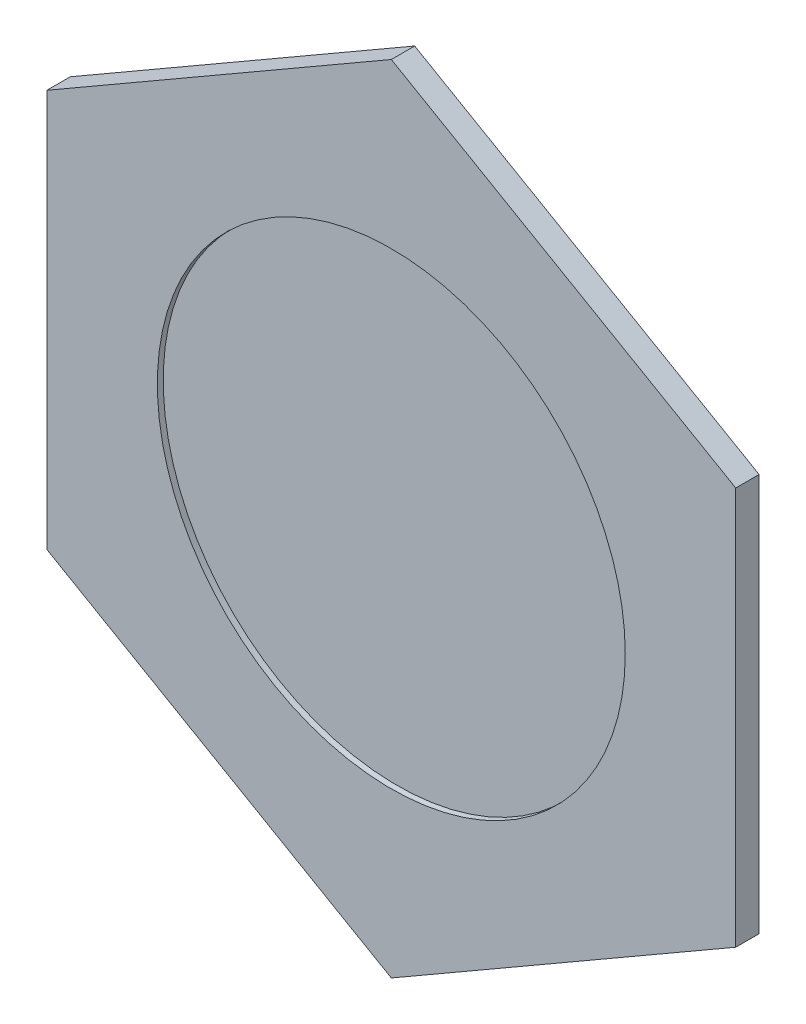
SolidWorks part; units mm, degrees
ref_plane "정면" through (0, 0, 0) normal (0, 0, 1) x (1, 0, 0)
ref_plane "윗면" through (0, 0, 0) normal (0, 1, 0) x (1, 0, 0)
ref_plane "우측면" through (0, 0, 0) normal (1, 0, 0) x (0, 0, -1)
sketch "스케치1" plane through (0, 0, 0) normal (0, 0, 1) x (1, 0, 0)
  line L0 (0, 0) -> (-56.2917, 32.5)
  line L1 (58.8897, -34) -> (58.8897, 34)
  line L2 (58.8897, 34) -> (0, 68)
  line L3 (0, 68) -> (-58.8897, 34)
  line L4 (-58.8897, 34) -> (-58.8897, -34)
  line L5 (-58.8897, -34) -> (0, -68)
  line L6 (0, -68) -> (58.8897, -34)
  line L7 (56.2917, 32.5) -> (0, 0)
  line L8 (0, -65) -> (0, 0)
  line L9 (-56.2917, 32.5) -> (-56.2917, -32.5)
  line L10 (-56.2917, -32.5) -> (0, -65)
  line L11 (0, -65) -> (56.2917, -32.5)
  line L12 (56.2917, -32.5) -> (56.2917, 32.5)
  line L13 (56.2917, 32.5) -> (0, 65)
  line L14 (0, 65) -> (-56.2917, 32.5)
  circle A1 centre (0, 0) radius 58.8897 construction
  point P1 (-58, 34.641)
  point P11 (0, -5)
  point P15 (0, -10)
  point P17 (-59, 32.909)
  point P20 (0, -15)
  point P21 (0, -20)
  point P22 (0, -25)
  point P23 (0, -30)
  point P24 (0, -35)
  point P25 (0, -40)
  point P26 (0, -45)
  point P27 (0, -50)
  point P28 (0, -55)
  point P29 (0, -60)
  point P32 (-4.3301, 2.3594)
  point P33 (-8.6603, 4.8594)
  point P34 (-12.9904, 7.3594)
  point P35 (-17.3205, 9.8594)
  point P36 (-21.6506, 12.3594)
  point P37 (-25.9808, 14.8594)
  point P38 (-30.3109, 17.3594)
  point P39 (-34.641, 19.8594)
  point P40 (-38.9711, 22.3594)
  point P41 (-43.3013, 24.8594)
  point P42 (-47.6314, 27.3594)
  point P43 (-51.9615, 29.8594)
  point P44 (4.2083, 2.4297)
  point P45 (8.5385, 4.9297)
  point P46 (12.8686, 7.4297)
  point P47 (17.1987, 9.9297)
  point P48 (21.5289, 12.4297)
  point P49 (25.859, 14.9297)
  point P50 (30.1891, 17.4297)
  point P51 (34.5192, 19.9297)
  point P52 (38.8494, 22.4297)
  point P53 (43.1795, 24.9297)
  point P54 (47.5096, 27.4297)
  point P55 (51.8397, 29.9297)
  point P56 (-0.0406, -0.0703)
  dimension "D1" = 65
  dimension "D2" = 5
  dimension "D3" = 12
  dimension "D4" = 3
  dimension "D5" = 65
  dimension "D6" = 65
  dimension "D7" = 65
  dimension "D8" = 68
extrude "보스-돌출1" add sketch "스케치1" along normal blind 4 contours L4 L5 L6 L1 L2 L3
sketch "스케치2" plane through (0, 0, 4) normal (0, 0, 1) x (1, 0, 0)
  circle A0 centre (0, 0) radius 40
  dimension "D1" = 80
extrude "컷-돌출1" cut sketch "스케치2" against normal blind 1
sketch "스케치4" plane through (0, 0, 4) normal (0, 0, 1) x (1, 0, 0)
  line L0 (0, 0) -> (0, -68)
  line L1 (0, 0) -> (-58.8897, 34)
  line L2 (0, 0) -> (58.8897, 34)
  line L3 (-58.8897, 34) -> (-58.8897, -34)
  line L4 (-58.8897, -34) -> (0, -68)
  line L5 (58.8897, -34) -> (0, -68)
  line L6 (58.8897, 34) -> (58.8897, -34)
  line L7 (58.8897, 34) -> (0, 68)
  line L8 (0, 68) -> (-58.8897, 34)
  line L9 (-56.3897, 32.5566) -> (56.3897, 32.5566) construction
  line L10 (0, 68) -> (0, 0)
  line L11 (-28.1949, -48.8349) -> (28.1949, 48.8349) construction
  line L12 (-58.8897, -34) -> (0, 0)
  line L13 (58.8897, -34) -> (0, 0)
  line L14 (0, 65.1132) -> (-56.3897, 32.5566)
  line L15 (56.3897, 32.5566) -> (0, 65.1132)
  line L16 (56.3897, -32.5566) -> (56.3897, 32.5566)
  line L17 (0, -65.1132) -> (56.3897, -32.5566)
  line L18 (-56.3897, -32.5566) -> (0, -65.1132)
  line L19 (-56.3897, 32.5566) -> (-56.3897, -32.5566)
  line L20 (-56.3897, 32.5566) -> (0, -65.1132) construction
  line L21 (56.3897, 32.5566) -> (0, -65.1132) construction
  line L22 (0, 65.1132) -> (56.3897, -32.5566) construction
  line L23 (-56.3897, -32.5566) -> (56.3897, -32.5566) construction
  line L24 (0, 65.1132) -> (-56.3897, -32.5566) construction
  line L25 (0, -65.1132) -> (-4.3301, -2.5)
  line L26 (0, -60) -> (-8.6603, -5)
  line L27 (0, -55) -> (-12.9904, -7.5)
  line L28 (0, -50) -> (-17.3205, -10)
  line L29 (0, -45) -> (-21.6506, -12.5)
  line L30 (0, -40) -> (-25.9808, -15)
  line L31 (0, -35) -> (-30.3109, -17.5)
  line L32 (0, -30) -> (-34.641, -20)
  line L33 (0, -25) -> (-38.9711, -22.5)
  line L34 (0, -20) -> (-43.3013, -25)
  line L35 (0, -15) -> (-47.6314, -27.5)
  line L36 (0, -10) -> (-51.9615, -30)
  line L37 (0, -5) -> (-56.3897, -32.5566)
  line L38 (-56.3897, -32.5566) -> (0, -60)
  line L39 (-51.9615, -35.1132) -> (0, -55)
  line L40 (-47.6314, -37.6132) -> (0, -50)
  line L41 (-43.3013, -40.1132) -> (0, -45)
  line L42 (-38.9711, -42.6132) -> (0, -40)
  line L43 (-34.641, -45.1132) -> (0, -35)
  line L44 (-30.3109, -47.6132) -> (0, -30)
  line L45 (-25.9808, -50.1132) -> (0, -25)
  line L46 (-21.6506, -52.6132) -> (0, -20)
  line L47 (-17.3205, -55.1132) -> (0, -15)
  line L48 (-12.9904, -57.6132) -> (0, -10)
  line L49 (-8.6603, -60.1132) -> (0, -5)
  line L50 (-4.3301, -62.6132) -> (0, 0)
  line L51 (-52.0596, -35.0566) -> (0, 0)
  line L52 (-47.7295, -37.5566) -> (-4.3301, -2.5)
  line L53 (-43.3993, -40.0566) -> (-8.6603, -5)
  line L54 (-39.0692, -42.5566) -> (-12.9904, -7.5)
  line L55 (-34.7391, -45.0566) -> (-17.3205, -10)
  line L56 (-30.409, -47.5566) -> (-21.6506, -12.5)
  line L57 (-26.0788, -50.0566) -> (-25.9808, -15)
  line L58 (-21.7487, -52.5566) -> (-30.3109, -17.5)
  line L59 (-17.4186, -55.0566) -> (-34.641, -20)
  line L60 (-13.0885, -57.5566) -> (-38.9711, -22.5)
  line L61 (-8.7583, -60.0566) -> (-43.3013, -25)
  line L62 (-4.4282, -62.5566) -> (-47.6314, -27.5)
  line L63 (0, -65.1132) -> (-51.9615, -30)
  line L64 (-56.3897, -32.5566) -> (-4.3301, 2.5)
  line L65 (-51.9615, -30) -> (-8.6603, 5)
  line L66 (-47.6314, -27.5) -> (-12.9904, 7.5)
  line L67 (-43.3013, -25) -> (-17.3205, 10)
  line L68 (-38.9711, -22.5) -> (-21.6506, 12.5)
  line L69 (-34.641, -20) -> (-25.9808, 15)
  line L70 (-30.3109, -17.5) -> (-30.3109, 17.5)
  line L71 (-25.9808, -15) -> (-34.641, 20)
  line L72 (-21.6506, -12.5) -> (-38.9711, 22.5)
  line L73 (-17.3205, -10) -> (-43.3013, 25)
  line L74 (-12.9904, -7.5) -> (-47.6314, 27.5)
  line L75 (-8.6603, -5) -> (-51.9615, 30)
  line L76 (-4.3301, -2.5) -> (-56.3897, 32.5566)
  line L77 (-56.3897, 32.5566) -> (-51.9615, -30)
  line L78 (-56.3897, 27.4434) -> (-47.6314, -27.5)
  line L79 (-56.3897, 22.4434) -> (-43.3013, -25)
  line L80 (-56.3897, 17.4434) -> (-38.9711, -22.5)
  line L81 (-56.3897, 12.4434) -> (-34.641, -20)
  line L82 (-56.3897, 7.4434) -> (-30.3109, -17.5)
  line L83 (-56.3897, 2.4434) -> (-25.9808, -15)
  line L84 (-56.3897, -2.5566) -> (-21.6506, -12.5)
  line L85 (-56.3897, -7.5566) -> (-17.3205, -10)
  line L86 (-56.3897, -12.5566) -> (-12.9904, -7.5)
  line L87 (-56.3897, -17.5566) -> (-8.6603, -5)
  line L88 (-56.3897, -22.5566) -> (-4.3301, -2.5)
  line L89 (-56.3897, -27.5566) -> (0, 0)
  line L90 (-56.3897, 27.5566) -> (0, 0)
  line L91 (-56.3897, 22.5566) -> (-4.3301, 2.5)
  line L92 (-56.3897, 17.5566) -> (-8.6603, 5)
  line L93 (-56.3897, 12.5566) -> (-12.9904, 7.5)
  line L94 (-56.3897, 7.5566) -> (-17.3205, 10)
  line L95 (-56.3897, 2.5566) -> (-21.6506, 12.5)
  line L96 (-56.3897, -2.4434) -> (-25.9808, 15)
  line L97 (-56.3897, -7.4434) -> (-30.3109, 17.5)
  line L98 (-56.3897, -12.4434) -> (-34.641, 20)
  line L99 (-56.3897, -17.4434) -> (-38.9711, 22.5)
  line L100 (-56.3897, -22.4434) -> (-43.3013, 25)
  line L101 (-56.3897, -27.4434) -> (-47.6314, 27.5)
  line L102 (-56.3897, -32.5566) -> (-51.9615, 30)
  line L103 (-56.3897, 32.5566) -> (0, 5)
  line L104 (-51.9615, 30) -> (0, 10)
  line L105 (-47.6314, 27.5) -> (0, 15)
  line L106 (-43.3013, 25) -> (0, 20)
  line L107 (-38.9711, 22.5) -> (0, 25)
  line L108 (-34.641, 20) -> (0, 30)
  line L109 (-30.3109, 17.5) -> (0, 35)
  line L110 (-25.9808, 15) -> (0, 40)
  line L111 (-21.6506, 12.5) -> (0, 45)
  line L112 (-17.3205, 10) -> (0, 50)
  line L113 (-12.9904, 7.5) -> (0, 55)
  line L114 (-8.6603, 5) -> (0, 60)
  line L115 (-4.3301, 2.5) -> (0, 65.1132)
  line L116 (0, 65.1132) -> (-51.9615, 30)
  line L117 (-4.4282, 62.5566) -> (-47.6314, 27.5)
  line L118 (-8.7583, 60.0566) -> (-43.3013, 25)
  line L119 (-13.0885, 57.5566) -> (-38.9711, 22.5)
  line L120 (-17.4186, 55.0566) -> (-34.641, 20)
  line L121 (-21.7487, 52.5566) -> (-30.3109, 17.5)
  line L122 (-26.0788, 50.0566) -> (-25.9808, 15)
  line L123 (-30.409, 47.5566) -> (-21.6506, 12.5)
  line L124 (-34.7391, 45.0566) -> (-17.3205, 10)
  line L125 (-39.0692, 42.5566) -> (-12.9904, 7.5)
  line L126 (-43.3993, 40.0566) -> (-8.6603, 5)
  line L127 (-47.7295, 37.5566) -> (-4.3301, 2.5)
  line L128 (-52.0596, 35.0566) -> (0, 0)
  line L129 (-4.3301, 62.6132) -> (0, 0)
  line L130 (-8.6603, 60.1132) -> (0, 5)
  line L131 (-12.9904, 57.6132) -> (0, 10)
  line L132 (-17.3205, 55.1132) -> (0, 15)
  line L133 (-21.6506, 52.6132) -> (0, 20)
  line L134 (-25.9808, 50.1132) -> (0, 25)
  line L135 (-30.3109, 47.6132) -> (0, 30)
  line L136 (-34.641, 45.1132) -> (0, 35)
  line L137 (-38.9711, 42.6132) -> (0, 40)
  line L138 (-43.3013, 40.1132) -> (0, 45)
  line L139 (-47.6314, 37.6132) -> (0, 50)
  line L140 (-51.9615, 35.1132) -> (0, 55)
  line L141 (-56.3897, 32.5566) -> (0, 60)
  line L142 (0, 65.1132) -> (4.3301, 2.5)
  line L143 (0, 60) -> (8.6603, 5)
  line L144 (0, 55) -> (12.9904, 7.5)
  line L145 (0, 50) -> (17.3205, 10)
  line L146 (0, 45) -> (21.6506, 12.5)
  line L147 (0, 40) -> (25.9808, 15)
  line L148 (0, 35) -> (30.3109, 17.5)
  line L149 (0, 30) -> (34.641, 20)
  line L150 (0, 25) -> (38.9711, 22.5)
  line L151 (0, 20) -> (43.3013, 25)
  line L152 (0, 15) -> (47.6314, 27.5)
  line L153 (0, 10) -> (51.9615, 30)
  line L154 (0, 5) -> (56.3897, 32.5566)
  line L155 (56.3897, 32.5566) -> (0, 60)
  line L156 (51.9615, 35.1132) -> (0, 55)
  line L157 (47.6314, 37.6132) -> (0, 50)
  line L158 (43.3013, 40.1132) -> (0, 45)
  line L159 (38.9711, 42.6132) -> (0, 40)
  line L160 (34.641, 45.1132) -> (0, 35)
  line L161 (30.3109, 47.6132) -> (0, 30)
  line L162 (25.9808, 50.1132) -> (0, 25)
  line L163 (21.6506, 52.6132) -> (0, 20)
  line L164 (17.3205, 55.1132) -> (0, 15)
  line L165 (12.9904, 57.6132) -> (0, 10)
  line L166 (8.6603, 60.1132) -> (0, 5)
  line L167 (4.3301, 62.6132) -> (0, 0)
  line L168 (52.0596, 35.0566) -> (0, 0)
  line L169 (47.7295, 37.5566) -> (4.3301, 2.5)
  line L170 (43.3993, 40.0566) -> (8.6603, 5)
  line L171 (39.0692, 42.5566) -> (12.9904, 7.5)
  line L172 (34.7391, 45.0566) -> (17.3205, 10)
  line L173 (30.409, 47.5566) -> (21.6506, 12.5)
  line L174 (26.0788, 50.0566) -> (25.9808, 15)
  line L175 (21.7487, 52.5566) -> (30.3109, 17.5)
  line L176 (17.4186, 55.0566) -> (34.641, 20)
  line L177 (13.0885, 57.5566) -> (38.9711, 22.5)
  line L178 (8.7583, 60.0566) -> (43.3013, 25)
  line L179 (4.4282, 62.5566) -> (47.6314, 27.5)
  line L180 (0, 65.1132) -> (51.9615, 30)
  line L181 (56.3897, 32.5566) -> (4.3301, -2.5)
  line L182 (51.9615, 30) -> (8.6603, -5)
  line L183 (47.6314, 27.5) -> (12.9904, -7.5)
  line L184 (43.3013, 25) -> (17.3205, -10)
  line L185 (38.9711, 22.5) -> (21.6506, -12.5)
  line L186 (34.641, 20) -> (25.9808, -15)
  line L187 (30.3109, 17.5) -> (30.3109, -17.5)
  line L188 (25.9808, 15) -> (34.641, -20)
  line L189 (21.6506, 12.5) -> (38.9711, -22.5)
  line L190 (17.3205, 10) -> (43.3013, -25)
  line L191 (12.9904, 7.5) -> (47.6314, -27.5)
  line L192 (8.6603, 5) -> (51.9615, -30)
  line L193 (4.3301, 2.5) -> (56.3897, -32.5566)
  line L194 (56.3897, -32.5566) -> (51.9615, 30)
  line L195 (56.3897, -27.4434) -> (47.6314, 27.5)
  line L196 (56.3897, -22.4434) -> (43.3013, 25)
  line L197 (56.3897, -17.4434) -> (38.9711, 22.5)
  line L198 (56.3897, -12.4434) -> (34.641, 20)
  line L199 (56.3897, -7.4434) -> (30.3109, 17.5)
  line L200 (56.3897, -2.4434) -> (25.9808, 15)
  line L201 (56.3897, 2.5566) -> (21.6506, 12.5)
  line L202 (56.3897, 7.5566) -> (17.3205, 10)
  line L203 (56.3897, 12.5566) -> (12.9904, 7.5)
  line L204 (56.3897, 17.5566) -> (8.6603, 5)
  line L205 (56.3897, 22.5566) -> (4.3301, 2.5)
  line L206 (56.3897, 27.5566) -> (0, 0)
  line L207 (56.3897, -27.5566) -> (0, 0)
  line L208 (56.3897, -22.5566) -> (4.3301, -2.5)
  line L209 (56.3897, -17.5566) -> (8.6603, -5)
  line L210 (56.3897, -12.5566) -> (12.9904, -7.5)
  line L211 (56.3897, -7.5566) -> (17.3205, -10)
  line L212 (56.3897, -2.5566) -> (21.6506, -12.5)
  line L213 (56.3897, 2.4434) -> (25.9808, -15)
  line L214 (56.3897, 7.4434) -> (30.3109, -17.5)
  line L215 (56.3897, 12.4434) -> (34.641, -20)
  line L216 (56.3897, 17.4434) -> (38.9711, -22.5)
  line L217 (56.3897, 22.4434) -> (43.3013, -25)
  line L218 (56.3897, 27.4434) -> (47.6314, -27.5)
  line L219 (56.3897, 32.5566) -> (51.9615, -30)
  line L220 (56.3897, -32.5566) -> (0, -5)
  line L221 (51.9615, -30) -> (0, -10)
  line L222 (47.6314, -27.5) -> (0, -15)
  line L223 (43.3013, -25) -> (0, -20)
  line L224 (38.9711, -22.5) -> (0, -25)
  line L225 (34.641, -20) -> (0, -30)
  line L226 (30.3109, -17.5) -> (0, -35)
  line L227 (25.9808, -15) -> (0, -40)
  line L228 (21.6506, -12.5) -> (0, -45)
  line L229 (17.3205, -10) -> (0, -50)
  line L230 (12.9904, -7.5) -> (0, -55)
  line L231 (8.6603, -5) -> (0, -60)
  line L232 (4.3301, -2.5) -> (0, -65.1132)
  line L233 (0, -65.1132) -> (51.9615, -30)
  line L234 (4.4282, -62.5566) -> (47.6314, -27.5)
  line L235 (8.7583, -60.0566) -> (43.3013, -25)
  line L236 (13.0885, -57.5566) -> (38.9711, -22.5)
  line L237 (17.4186, -55.0566) -> (34.641, -20)
  line L238 (21.7487, -52.5566) -> (30.3109, -17.5)
  line L239 (26.0788, -50.0566) -> (25.9808, -15)
  line L240 (30.409, -47.5566) -> (21.6506, -12.5)
  line L241 (34.7391, -45.0566) -> (17.3205, -10)
  line L242 (39.0692, -42.5566) -> (12.9904, -7.5)
  line L243 (43.3993, -40.0566) -> (8.6603, -5)
  line L244 (47.7295, -37.5566) -> (4.3301, -2.5)
  line L245 (52.0596, -35.0566) -> (0, 0)
  line L246 (4.3301, -62.6132) -> (0, 0)
  line L247 (8.6603, -60.1132) -> (0, -5)
  line L248 (12.9904, -57.6132) -> (0, -10)
  line L249 (17.3205, -55.1132) -> (0, -15)
  line L250 (21.6506, -52.6132) -> (0, -20)
  line L251 (25.9808, -50.1132) -> (0, -25)
  line L252 (30.3109, -47.6132) -> (0, -30)
  line L253 (34.641, -45.1132) -> (0, -35)
  line L254 (38.9711, -42.6132) -> (0, -40)
  line L255 (43.3013, -40.1132) -> (0, -45)
  line L256 (47.6314, -37.6132) -> (0, -50)
  line L257 (51.9615, -35.1132) -> (0, -55)
  line L258 (56.3897, -32.5566) -> (0, -60)
  circle A0 centre (0, 0) radius 40
  point P15 (-4.4282, 62.5566)
  point P18 (0, 5)
  point P19 (-8.7583, 60.0566)
  point P20 (-13.0885, 57.5566)
  point P22 (0, 10)
  point P24 (0, 15)
  point P26 (0, 20)
  point P28 (0, 25)
  point P29 (0, 30)
  point P30 (0, 35)
  point P31 (0, 0)
  point P32 (0, 40)
  point P33 (0, 45)
  point P34 (0, 50)
  point P35 (0, 55)
  point P36 (0, 60)
  point P37 (-21.7487, 52.5566)
  point P38 (4.3301, 2.5)
  point P39 (8.6603, 5)
  point P40 (12.9904, 7.5)
  point P41 (17.3205, 10)
  point P42 (21.6506, 12.5)
  point P43 (25.9808, 15)
  point P44 (30.3109, 17.5)
  point P45 (34.641, 20)
  point P46 (38.9711, 22.5)
  point P47 (43.3013, 25)
  point P48 (47.6314, 27.5)
  point P49 (51.9615, 30)
  point P50 (4.3301, -2.5)
  point P51 (8.6603, -5)
  point P52 (12.9904, -7.5)
  point P53 (17.3205, -10)
  point P54 (21.6506, -12.5)
  point P55 (25.9808, -15)
  point P56 (30.3109, -17.5)
  point P57 (34.641, -20)
  point P58 (38.9711, -22.5)
  point P59 (43.3013, -25)
  point P60 (47.6314, -27.5)
  point P61 (51.9615, -30)
  point P62 (0, -5)
  point P63 (0, -10)
  point P64 (0, -15)
  point P65 (0, -20)
  point P66 (0, -25)
  point P67 (0, -30)
  point P68 (0, -35)
  point P69 (0, -40)
  point P70 (0, -45)
  point P71 (0, -50)
  point P72 (0, -55)
  point P73 (0, -60)
  point P74 (-4.3301, -2.5)
  point P75 (-8.6603, -5)
  point P76 (-12.9904, -7.5)
  point P77 (-17.3205, -10)
  point P78 (-21.6506, -12.5)
  point P79 (-25.9808, -15)
  point P80 (-30.3109, -17.5)
  point P81 (-34.641, -20)
  point P82 (-38.9711, -22.5)
  point P83 (-43.3013, -25)
  point P84 (-47.6314, -27.5)
  point P85 (-51.9615, -30)
  point P86 (-4.3301, 2.5)
  point P87 (-8.6603, 5)
  point P88 (-12.9904, 7.5)
  point P89 (-17.3205, 10)
  point P90 (-21.6506, 12.5)
  point P91 (-25.9808, 15)
  point P92 (-30.3109, 17.5)
  point P93 (-34.641, 20)
  point P94 (-38.9711, 22.5)
  point P95 (-43.3013, 25)
  point P96 (-47.6314, 27.5)
  point P97 (-51.9615, 30)
  point P98 (0, 0)
  point P99 (-26.0788, 50.0566)
  point P100 (-30.409, 47.5566)
  point P101 (-34.7391, 45.0566)
  point P102 (-39.0692, 42.5566)
  point P103 (-43.3993, 40.0566)
  point P104 (-47.7295, 37.5566)
  point P105 (-52.0596, 35.0566)
  point P106 (-17.4186, 55.0566)
  point P107 (51.9615, 35.1132)
  point P110 (47.6314, 37.6132)
  point P111 (43.3013, 40.1132)
  point P112 (34.641, 45.1132)
  point P113 (30.3109, 47.6132)
  point P114 (25.9808, 50.1132)
  point P115 (21.6506, 52.6132)
  point P116 (17.3205, 55.1132)
  point P117 (12.9904, 57.6132)
  point P118 (8.6603, 60.1132)
  point P119 (4.3301, 62.6132)
  point P120 (38.9711, 42.6132)
  point P121 (56.3897, -27.4434)
  point P122 (56.3897, -22.4434)
  point P123 (56.3897, -17.4434)
  point P124 (56.3897, -7.4434)
  point P125 (56.3897, -2.4434)
  point P126 (56.3897, 2.5566)
  point P127 (56.3897, 7.5566)
  point P128 (56.3897, 12.5566)
  point P129 (56.3897, 17.5566)
  point P130 (56.3897, 22.5566)
  point P131 (56.3897, 27.5566)
  point P132 (56.3897, -12.4434)
  point P133 (4.4282, -62.5566)
  point P134 (8.7583, -60.0566)
  point P135 (13.0885, -57.5566)
  point P136 (21.7487, -52.5566)
  point P137 (26.0788, -50.0566)
  point P138 (30.409, -47.5566)
  point P139 (34.7391, -45.0566)
  point P140 (39.0692, -42.5566)
  point P141 (43.3993, -40.0566)
  point P142 (47.7295, -37.5566)
  point P143 (52.0596, -35.0566)
  point P144 (17.4186, -55.0566)
  point P145 (-51.9615, -35.1132)
  point P146 (-47.6314, -37.6132)
  point P147 (-43.3013, -40.1132)
  point P148 (-34.641, -45.1132)
  point P149 (-30.3109, -47.6132)
  point P150 (-25.9808, -50.1132)
  point P151 (-21.6506, -52.6132)
  point P152 (-17.3205, -55.1132)
  point P153 (-12.9904, -57.6132)
  point P154 (-8.6603, -60.1132)
  point P155 (-4.3301, -62.6132)
  point P156 (-38.9711, -42.6132)
  point P157 (-56.3897, 27.4434)
  point P158 (-56.3897, 22.4434)
  point P159 (-56.3897, 17.4434)
  point P160 (-56.3897, 7.4434)
  point P161 (-56.3897, 2.4434)
  point P162 (-56.3897, -2.5566)
  point P163 (-56.3897, -7.5566)
  point P164 (-56.3897, -12.5566)
  point P165 (-56.3897, -17.5566)
  point P166 (-56.3897, -22.5566)
  point P167 (-56.3897, -27.5566)
  point P168 (-56.3897, 12.4434)
  point P169 (0, 0)
  point P222 (0, 0)
  point P223 (-4.3301, -2.5)
  point P224 (-8.6603, -5)
  point P225 (-12.9904, -7.5)
  point P226 (-17.3205, -10)
  point P227 (-21.6506, -12.5)
  point P228 (-25.9808, -15)
  point P229 (-30.3109, -17.5)
  point P230 (-34.641, -20)
  point P231 (-38.9711, -22.5)
  point P232 (-43.3013, -25)
  point P233 (-47.6314, -27.5)
  point P234 (-51.9615, -30)
  point P235 (-4.3301, 2.5)
  point P236 (-8.6603, 5)
  point P237 (-12.9904, 7.5)
  point P238 (-17.3205, 10)
  point P239 (-21.6506, 12.5)
  point P240 (-25.9808, 15)
  point P241 (-30.3109, 17.5)
  point P242 (-34.641, 20)
  point P243 (-38.9711, 22.5)
  point P244 (-43.3013, 25)
  point P245 (-47.6314, 27.5)
  point P246 (-51.9615, 30)
  point P247 (0, 0)
  point P250 (-56.3897, 27.4434)
  point P251 (-56.3897, 22.4434)
  point P252 (-56.3897, 17.4434)
  point P253 (-56.3897, 7.4434)
  point P254 (-56.3897, 2.4434)
  point P255 (-56.3897, -2.5566)
  point P256 (-56.3897, -7.5566)
  point P257 (-56.3897, -12.5566)
  point P258 (-56.3897, -17.5566)
  point P259 (-56.3897, -22.5566)
  point P260 (-56.3897, -27.5566)
  point P261 (-56.3897, 12.4434)
  point P262 (0, 0)
  point P311 (0, 0)
  point P312 (-4.3301, 2.5)
  point P313 (-8.6603, 5)
  point P314 (-12.9904, 7.5)
  point P315 (-17.3205, 10)
  point P316 (-21.6506, 12.5)
  point P317 (-25.9808, 15)
  point P318 (-30.3109, 17.5)
  point P319 (-34.641, 20)
  point P320 (-38.9711, 22.5)
  point P321 (-43.3013, 25)
  point P322 (-47.6314, 27.5)
  point P323 (-51.9615, 30)
  point P324 (0, 5)
  point P325 (0, 10)
  point P326 (0, 15)
  point P327 (0, 20)
  point P328 (0, 25)
  point P329 (0, 30)
  point P330 (0, 35)
  point P331 (0, 40)
  point P332 (0, 45)
  point P333 (0, 50)
  point P334 (0, 55)
  point P335 (0, 60)
  point P336 (0, 0)
  point P339 (-4.4282, 62.5566)
  point P340 (-8.7583, 60.0566)
  point P341 (-13.0885, 57.5566)
  point P342 (-21.7487, 52.5566)
  point P343 (-26.0788, 50.0566)
  point P344 (-30.409, 47.5566)
  point P345 (-34.7391, 45.0566)
  point P346 (-39.0692, 42.5566)
  point P347 (-43.3993, 40.0566)
  point P348 (-47.7295, 37.5566)
  point P349 (-52.0596, 35.0566)
  point P350 (-17.4186, 55.0566)
  point P351 (0, 0)
  point P400 (0, 0)
  point P401 (0, 5)
  point P402 (0, 10)
  point P403 (0, 15)
  point P404 (0, 20)
  point P405 (0, 25)
  point P406 (0, 30)
  point P407 (0, 35)
  point P408 (0, 40)
  point P409 (0, 45)
  point P410 (0, 50)
  point P411 (0, 55)
  point P412 (0, 60)
  point P413 (4.3301, 2.5)
  point P414 (8.6603, 5)
  point P415 (12.9904, 7.5)
  point P416 (17.3205, 10)
  point P417 (21.6506, 12.5)
  point P418 (25.9808, 15)
  point P419 (30.3109, 17.5)
  point P420 (34.641, 20)
  point P421 (38.9711, 22.5)
  point P422 (43.3013, 25)
  point P423 (47.6314, 27.5)
  point P424 (51.9615, 30)
  point P425 (0, 0)
  point P428 (51.9615, 35.1132)
  point P429 (47.6314, 37.6132)
  point P430 (43.3013, 40.1132)
  point P431 (34.641, 45.1132)
  point P432 (30.3109, 47.6132)
  point P433 (25.9808, 50.1132)
  point P434 (21.6506, 52.6132)
  point P435 (17.3205, 55.1132)
  point P436 (12.9904, 57.6132)
  point P437 (8.6603, 60.1132)
  point P438 (4.3301, 62.6132)
  point P439 (38.9711, 42.6132)
  point P440 (0, 0)
  point P489 (0, 0)
  point P490 (4.3301, 2.5)
  point P491 (8.6603, 5)
  point P492 (12.9904, 7.5)
  point P493 (17.3205, 10)
  point P494 (21.6506, 12.5)
  point P495 (25.9808, 15)
  point P496 (30.3109, 17.5)
  point P497 (34.641, 20)
  point P498 (38.9711, 22.5)
  point P499 (43.3013, 25)
  point P500 (47.6314, 27.5)
  point P501 (51.9615, 30)
  point P502 (4.3301, -2.5)
  point P503 (8.6603, -5)
  point P504 (12.9904, -7.5)
  point P505 (17.3205, -10)
  point P506 (21.6506, -12.5)
  point P507 (25.9808, -15)
  point P508 (30.3109, -17.5)
  point P509 (34.641, -20)
  point P510 (38.9711, -22.5)
  point P511 (43.3013, -25)
  point P512 (47.6314, -27.5)
  point P513 (51.9615, -30)
  point P514 (0, 0)
  point P517 (56.3897, -27.4434)
  point P518 (56.3897, -22.4434)
  point P519 (56.3897, -17.4434)
  point P520 (56.3897, -7.4434)
  point P521 (56.3897, -2.4434)
  point P522 (56.3897, 2.5566)
  point P523 (56.3897, 7.5566)
  point P524 (56.3897, 12.5566)
  point P525 (56.3897, 17.5566)
  point P526 (56.3897, 22.5566)
  point P527 (56.3897, 27.5566)
  point P528 (56.3897, -12.4434)
  point P529 (0, 0)
  point P578 (0, 0)
  point P579 (4.3301, -2.5)
  point P580 (8.6603, -5)
  point P581 (12.9904, -7.5)
  point P582 (17.3205, -10)
  point P583 (21.6506, -12.5)
  point P584 (25.9808, -15)
  point P585 (30.3109, -17.5)
  point P586 (34.641, -20)
  point P587 (38.9711, -22.5)
  point P588 (43.3013, -25)
  point P589 (47.6314, -27.5)
  point P590 (51.9615, -30)
  point P591 (0, -5)
  point P592 (0, -10)
  point P593 (0, -15)
  point P594 (0, -20)
  point P595 (0, -25)
  point P596 (0, -30)
  point P597 (0, -35)
  point P598 (0, -40)
  point P599 (0, -45)
  point P600 (0, -50)
  point P601 (0, -55)
  point P602 (0, -60)
  point P603 (0, 0)
  point P606 (4.4282, -62.5566)
  point P607 (8.7583, -60.0566)
  point P608 (13.0885, -57.5566)
  point P609 (21.7487, -52.5566)
  point P610 (26.0788, -50.0566)
  point P611 (30.409, -47.5566)
  point P612 (34.7391, -45.0566)
  point P613 (39.0692, -42.5566)
  point P614 (43.3993, -40.0566)
  point P615 (47.7295, -37.5566)
  point P616 (52.0596, -35.0566)
  point P617 (17.4186, -55.0566)
  point P618 (0, 0)
  point P665 (0, 0)
  dimension "D1" = 2.5
  dimension "D3" = 5
  dimension "D4" = 12
  dimension "D2" = 6
  dimension "D6" = 6
  dimension "D7" = 6
